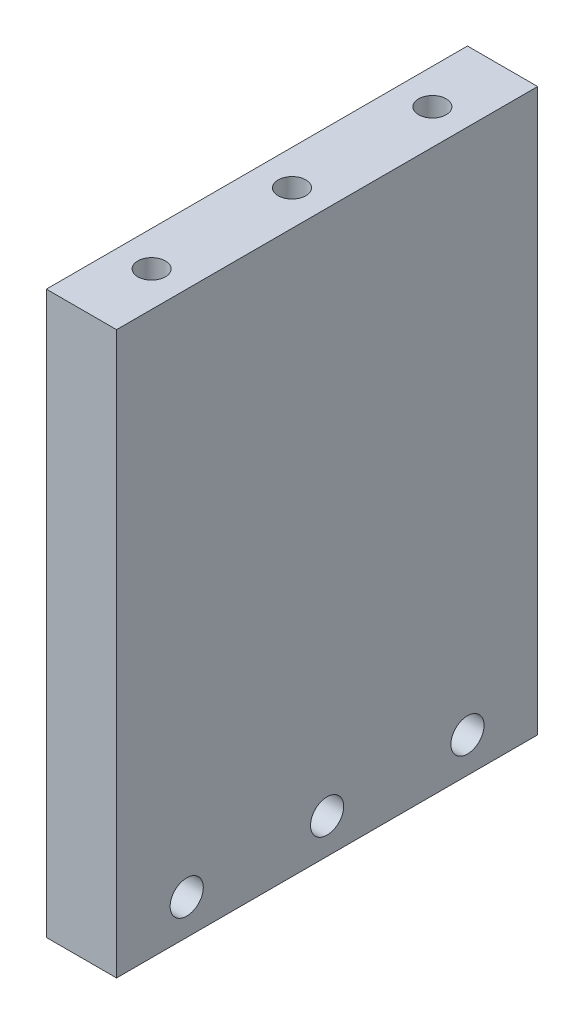
SolidWorks part; units mm, degrees
ref_plane "Front Plane" through (0, 0, 0) normal (0, 0, 1) x (1, 0, 0)
ref_plane "Top Plane" through (0, 0, 0) normal (0, 1, 0) x (1, 0, 0)
ref_plane "Right Plane" through (0, 0, 0) normal (1, 0, 0) x (0, 0, -1)
sketch "Sketch1" plane through (0, 0, 0) normal (0, 0, 1) x (1, 0, 0)
  line L1 (0, 0) -> (6.35, 0)
  line L2 (0, 0) -> (0, 50.8)
  line L3 (0, 50.8) -> (6.35, 50.8)
  line L4 (6.35, 0) -> (6.35, 50.8)
extrude "Boss-Extrude1" add sketch "Sketch1" along normal blind 38.1
sketch "Sketch2" plane through (6.35, 0, 0) normal (1, 0, 0) x (0, 0, -1)
  line L0 (0, 0) -> (0, 50.8) construction
  line L1 (-38.1, 0) -> (0, 0)
  line L2 (-38.1, 0) -> (-38.1, 6.35)
  line L3 (-38.1, 6.35) -> (0, 6.35)
  line L4 (0, 0) -> (0, 6.35)
  line L5 (-38.1, 3.175) -> (-31.75, 3.175)
  line L6 (0, 3.175) -> (-6.35, 3.175)
  line L7 (-31.75, 3.175) -> (-6.35, 3.175)
  circle A0 centre (-31.75, 3.175) radius 1.5
  circle A1 centre (-19.05, 3.175) radius 1.5
  circle A2 centre (-6.35, 3.175) radius 1.5
  dimension "D3" = 3
  dimension "D4" = 3
  dimension "D5" = 3
  dimension "D1" = 6.35
  dimension "D2" = 6.35
extrude "Cut-Extrude1" cut sketch "Sketch2" against normal blind 6.35 contours L7 A2 L6 | L6 A2 L7 | L7 A1 | L5 A0 L7
sketch "Sketch3" plane through (0, 50.8, 0) normal (0, 1, 0) x (1, 0, 0)
  line L0 (3.175, 0) -> (3.175, -38.1)
  line L1 (0, 0) -> (6.35, 0)
  line L2 (0, 0) -> (0, -38.1)
  line L3 (0, -38.1) -> (6.35, -38.1)
  line L4 (6.35, 0) -> (6.35, -38.1)
  line L5 (3.175, -38.1) -> (3.175, -31.75)
  line L6 (3.175, -31.75) -> (3.175, -6.35)
  line L7 (3.175, -6.35) -> (3.175, 0)
  circle A0 centre (3.175, -6.35) radius 1.25
  circle A1 centre (3.175, -19.05) radius 1.25
  circle A2 centre (3.175, -31.75) radius 1.25
  dimension "D3" = 2.5
  dimension "D4" = 2.5
  dimension "D5" = 2.5
  dimension "D1" = 6.35
  dimension "D2" = 6.35
extrude "Cut-Extrude2" cut sketch "Sketch3" against normal blind 6.35 contours L0 A0 L7 | L7 A0 L0 | L0 A1 | L0 A2 | L0 A2
